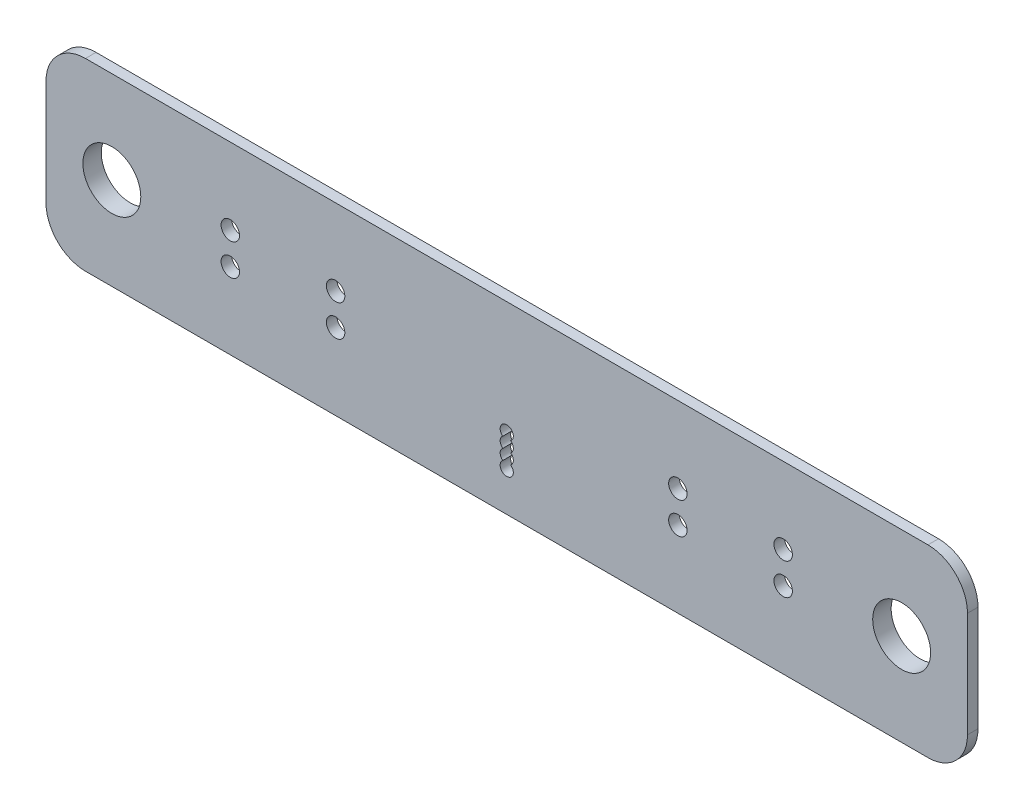
SolidWorks part; units mm, degrees
ref_plane "Ön Düzlem" through (0, 0, 0) normal (0, 0, 1) x (1, 0, 0)
ref_plane "Üst Düzlem" through (0, 0, 0) normal (0, 1, 0) x (1, 0, 0)
ref_plane "Sağ Düzlem" through (0, 0, 0) normal (1, 0, 0) x (0, 0, -1)
sketch "Sketch1" plane through (0, 0, 0) normal (0, 0, 1) x (1, 0, 0)
  line L1 (-175, 35) -> (175, 35)
  line L2 (-175, 35) -> (-175, -35)
  line L3 (-175, -35) -> (175, -35)
  line L4 (175, 35) -> (175, -35)
  line L5 (-175, 35) -> (175, -35) construction
  line L6 (-175, -35) -> (175, 35) construction
  point P0 (0, 0)
  dimension "D1" = 70
  dimension "D2" = 350
extrude "Boss-Extrude1" add sketch "Sketch1" along normal blind 4
fillet "Fillet1" radius 15 4 edges at (175, -35, 2) (175, 35, 2) (-175, -35, 2) (-175, 35, 2)
sketch "Sketch2" plane through (0, 0, 0) normal (0, 0, -1) x (-1, 0, 0)
  line L0 (-175, -20) -> (-175, 20) construction
  circle A0 centre (-150, 0) radius 11
  dimension "D1" = 25
  dimension "D2" = 22
extrude "Cut-Extrude1" cut sketch "Sketch2" against normal blind 10
sketch "Sketch3" plane through (0, 0, 0) normal (0, 0, -1) x (-1, 0, 0)
  circle A0 centre (-150, 0) radius 11
  circle A1 centre (-150, 0) radius 13.5
  dimension "D1" = 27
  dimension "D2" = 22
extrude "Boss-Extrude2" add sketch "Sketch3" along normal blind 3
mirror "Mirror2" about plane through (0, 0, 0) normal (1, 0, 0) of "Cut-Extrude1", "Boss-Extrude2"
sketch "Sketch4" plane through (0, 0, 4) normal (0, 0, 1) x (1, 0, 0)
  circle A6 centre (-105, 6) radius 3.5
  circle A7 centre (-105, -6) radius 3.5
  circle A8 centre (-65, -6) radius 3.5
  circle A9 centre (-65, 6) radius 3.5
  circle A10 centre (65, 6) radius 3.5
  circle A11 centre (65, -6) radius 3.5
  circle A12 centre (105, -6) radius 3.5
  circle A13 centre (105, 6) radius 3.5
  circle A14 centre (150, 0) radius 11 construction
  circle A15 centre (-150, 0) radius 11 construction
  arc A16 (-1.5, -14) -> (-1.5, -10) centre (0, -12) cw
  arc A17 (1.5, -14) -> (1.5, -18) centre (0, -16) cw
  arc A18 (-1.5, -10) -> (1.5, -10) centre (0, -8) cw
  arc A19 (1.5, -10) -> (1.5, -14) centre (0, -12) cw
  arc A20 (-1.5, -18) -> (-1.5, -14) centre (0, -16) cw
  arc A21 (1.5, -18) -> (-1.5, -18) centre (0, -20) cw
  dimension "D4" = 12
  dimension "D5" = 12
  dimension "D6" = 12
  dimension "D2" = 12
  dimension "D7" = 6
  dimension "D8" = 6
  dimension "D9" = 45
  dimension "D10" = 40
  dimension "D11" = 6
  dimension "D12" = 45
  dimension "D13" = 40
extrude "Cut-Extrude3" cut sketch "Sketch4" against normal blind 10
